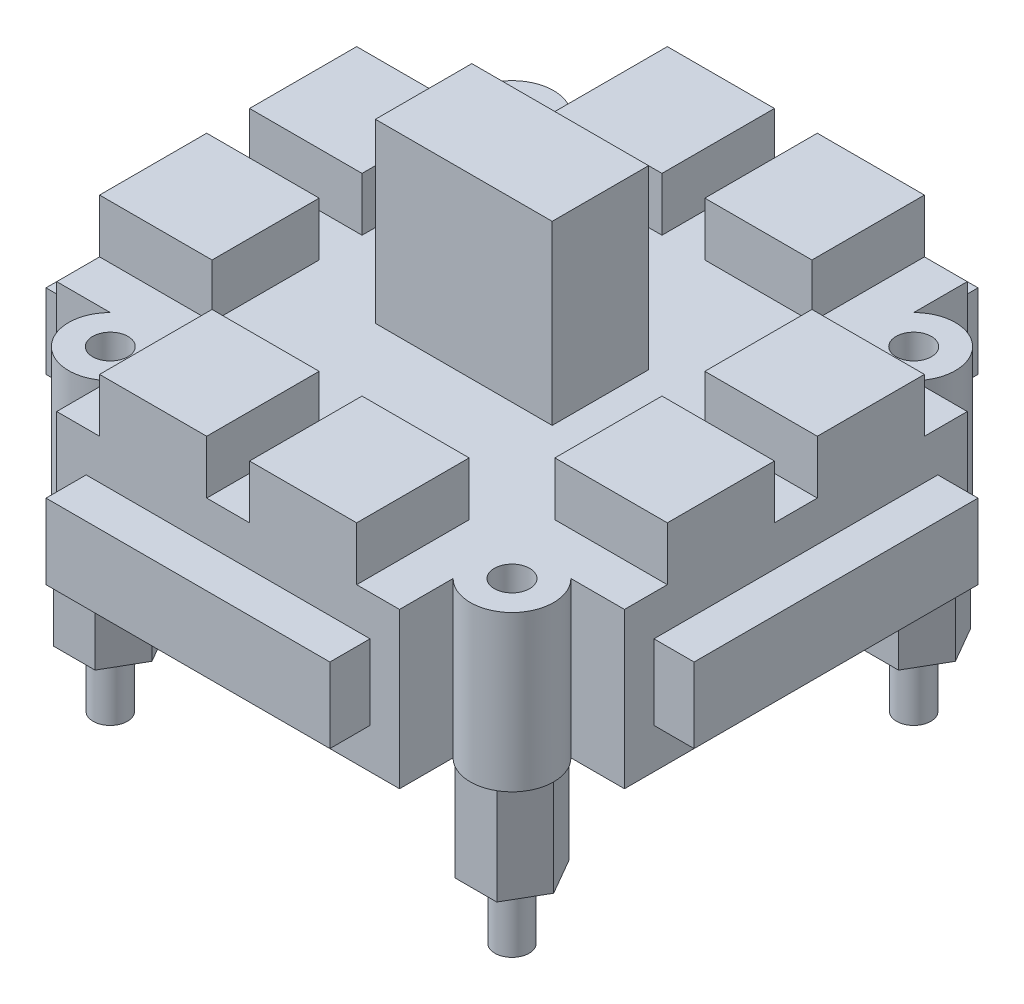
SolidWorks part; units mm, degrees
ref_plane "前视基准面" through (0, 0, 0) normal (0, 0, 1) x (1, 0, 0)
ref_plane "上视基准面" through (0, 0, 0) normal (0, 1, 0) x (1, 0, 0)
ref_plane "右视基准面" through (0, 0, 0) normal (1, 0, 0) x (0, 0, -1)
other "Configuration Table"
sketch "草图1" plane through (0, 0, 0) normal (0, 1, 0) x (1, 0, 0)
  line L1 (-18.75, -18.75) -> (18.75, -18.75) construction
  line L2 (-18.75, -18.75) -> (-18.75, 18.75) construction
  line L3 (-18.75, 18.75) -> (18.75, 18.75) construction
  line L4 (18.75, -18.75) -> (18.75, 18.75) construction
  line L5 (-18.75, -18.75) -> (18.75, 18.75) construction
  line L6 (-18.75, 18.75) -> (18.75, -18.75) construction
  line L7 (-16, -26.5) -> (16, -26.5) construction
  line L8 (-16, -26.5) -> (-16, 26.5) construction
  line L9 (-16, 26.5) -> (16, 26.5) construction
  line L10 (16, -26.5) -> (16, 26.5) construction
  line L11 (-16, -26.5) -> (16, 26.5) construction
  line L12 (-16, 26.5) -> (16, -26.5) construction
  line L13 (-26.5, -16) -> (26.5, -16) construction
  line L14 (-26.5, -16) -> (-26.5, 16) construction
  line L15 (-26.5, 16) -> (26.5, 16) construction
  line L16 (26.5, -16) -> (26.5, 16) construction
  line L17 (-26.5, -16) -> (26.5, 16) construction
  line L18 (-26.5, 16) -> (26.5, -16) construction
  circle A0 centre (-18.75, 18.75) radius 1.65
  circle A1 centre (18.75, 18.75) radius 1.65
  circle A2 centre (18.75, -18.75) radius 1.65
  circle A3 centre (-18.75, -18.75) radius 1.65
  circle A4 centre (-18.75, 18.75) radius 3.8891
  circle A5 centre (18.75, 18.75) radius 3.8891
  circle A6 centre (18.75, -18.75) radius 3.8891
  circle A7 centre (-18.75, -18.75) radius 3.8891
  point P0 (0, 0)
  point P10 (0, 0)
  point P15 (0, 0)
  point P24 (-16, 16)
  dimension "D3" = 3.3
  dimension "D1" = 37.5
  dimension "D2" = 37.5
  dimension "D4" = 32
  dimension "D5" = 53
  dimension "D6" = 32
  dimension "D7" = 53
extrude "凸台-拉伸2" add sketch "草图1" along normal mid plane 14.5
sketch "草图2" plane through (0, 0, 0) normal (0, 1, 0) x (1, 0, 0)
  line L1 (-16, -26.5) -> (16, -26.5)
  line L2 (-16, -26.5) -> (-16, 26.5)
  line L3 (-16, 26.5) -> (16, 26.5)
  line L4 (16, -26.5) -> (16, 26.5)
  line L5 (-16, -26.5) -> (16, 26.5) construction
  line L6 (-16, 26.5) -> (16, -26.5) construction
  line L7 (-26.5, -16) -> (26.5, -16)
  line L8 (-26.5, -16) -> (-26.5, 16)
  line L9 (-26.5, 16) -> (26.5, 16)
  line L10 (26.5, -16) -> (26.5, 16)
  line L11 (-26.5, -16) -> (26.5, 16) construction
  line L12 (-26.5, 16) -> (26.5, -16) construction
  circle A1 centre (-18.75, -18.75) radius 1.65
  circle A2 centre (-18.75, -18.75) radius 1.65 construction
  circle A3 centre (18.75, -18.75) radius 1.65
  circle A4 centre (18.75, -18.75) radius 1.65 construction
  circle A5 centre (18.75, 18.75) radius 1.65
  circle A6 centre (18.75, 18.75) radius 1.65 construction
  circle A7 centre (-18.75, 18.75) radius 1.65
  circle A8 centre (-18.75, 18.75) radius 1.65 construction
  circle A9 centre (-18.75, -18.75) radius 3.8891
  circle A10 centre (-18.75, -18.75) radius 3.8891 construction
  circle A11 centre (18.75, -18.75) radius 3.8891
  circle A12 centre (18.75, -18.75) radius 3.8891 construction
  circle A13 centre (18.75, 18.75) radius 3.8891
  circle A14 centre (18.75, 18.75) radius 3.8891 construction
  circle A15 centre (-18.75, 18.75) radius 3.8891
  circle A16 centre (-18.75, 18.75) radius 3.8891 construction
  point P0 (0, 0)
  point P6 (0, 0)
  dimension "D9" = 32
  dimension "D10" = 53
  dimension "D11" = 32
  dimension "D12" = 53
  dimension "D1" = 0
  dimension "D2" = 0
  dimension "D3" = 0
  dimension "D4" = 0
  dimension "D5" = 0
  dimension "D6" = 0
  dimension "D7" = 0
  dimension "D8" = 0
extrude "凸台-拉伸3" add sketch "草图2" along normal mid plane 14.5 contours L9 L8 L7 L2 | L9 L2 L7 L4 | L2 L9 L4 L3 | L7 L10 L9 L4 | L7 L2 L1 L4
sketch "草图3" plane through (0, 0, 0) normal (0, 1, 0) x (1, 0, 0)
  line L1 (-13.25, -30.25) -> (13.25, -30.25)
  line L2 (-13.25, -30.25) -> (-13.25, 30.25)
  line L3 (-13.25, 30.25) -> (13.25, 30.25)
  line L4 (13.25, -30.25) -> (13.25, 30.25)
  line L5 (-13.25, -30.25) -> (13.25, 30.25) construction
  line L6 (-13.25, 30.25) -> (13.25, -30.25) construction
  line L7 (-30.25, -13.25) -> (30.25, -13.25)
  line L8 (-30.25, -13.25) -> (-30.25, 13.25)
  line L9 (-30.25, 13.25) -> (30.25, 13.25)
  line L10 (30.25, -13.25) -> (30.25, 13.25)
  line L11 (-30.25, -13.25) -> (30.25, 13.25) construction
  line L12 (-30.25, 13.25) -> (30.25, -13.25) construction
  point P0 (0, 0)
  point P6 (0, 0)
  dimension "D1" = 26.5
  dimension "D2" = 60.5
  dimension "D3" = 26.5
  dimension "D4" = 60.5
extrude "凸台-拉伸4" add sketch "草图3" along normal mid plane 7 contours L7 L2 L1 L4 | L9 L8 L7 L2 | L2 L9 L4 L3
sketch "草图4" plane through (0, 7.25, 0) normal (0, 1, 0) x (1, 0, 0)
  line L1 (-8.25, -4.5) -> (8.25, -4.5)
  line L2 (-8.25, -4.5) -> (-8.25, 4.5)
  line L3 (-8.25, 4.5) -> (8.25, 4.5)
  line L4 (8.25, -4.5) -> (8.25, 4.5)
  line L5 (-8.25, -4.5) -> (8.25, 4.5) construction
  line L6 (-8.25, 4.5) -> (8.25, -4.5) construction
  point P0 (0, 0)
  dimension "D1" = 16.5
  dimension "D2" = 9
extrude "凸台-拉伸5" add sketch "草图4" along normal blind 16.5
sketch "草图5" plane through (0, 7.25, 0) normal (0, 1, 0) x (1, 0, 0)
  line L0 (-8.25, 0) -> (-26.5, 0) construction
  line L1 (-8.25, 4.5) -> (-8.25, -4.5) construction
  line L2 (-26.5, -16) -> (-26.5, 16) construction
  line L3 (-26.5, -13.25) -> (-26.5, 13.25) construction
  line L4 (-26.5, 2) -> (-16, 2)
  line L5 (-26.5, 2) -> (-26.5, 12)
  line L6 (-26.5, 12) -> (-16, 12)
  line L7 (-16, 2) -> (-16, 12)
  line L8 (-26.5, -12) -> (-16, -12)
  line L9 (-16, -2) -> (-16, -12)
  line L10 (-26.5, -2) -> (-16, -2)
  line L11 (-26.5, -2) -> (-26.5, -12)
  line L12 (2, 26.5) -> (12, 26.5)
  line L13 (2, 26.5) -> (2, 16)
  line L14 (2, 16) -> (12, 16)
  line L15 (12, 26.5) -> (12, 16)
  line L16 (-12, 26.5) -> (-12, 16)
  line L17 (-2, 16) -> (-12, 16)
  line L18 (-2, 26.5) -> (-2, 16)
  line L19 (-2, 26.5) -> (-12, 26.5)
  line L20 (26.5, -2) -> (26.5, -12)
  line L21 (26.5, -2) -> (16, -2)
  line L22 (16, -2) -> (16, -12)
  line L23 (26.5, -12) -> (16, -12)
  line L24 (26.5, 12) -> (16, 12)
  line L25 (16, 2) -> (16, 12)
  line L26 (26.5, 2) -> (16, 2)
  line L27 (26.5, 2) -> (26.5, 12)
  line L28 (-2, -26.5) -> (-12, -26.5)
  line L29 (-2, -26.5) -> (-2, -16)
  line L30 (-2, -16) -> (-12, -16)
  line L31 (-12, -26.5) -> (-12, -16)
  line L32 (12, -26.5) -> (12, -16)
  line L33 (2, -16) -> (12, -16)
  line L34 (2, -26.5) -> (2, -16)
  line L35 (2, -26.5) -> (12, -26.5)
  line L36 (-8.25, 0) -> (-16, 2) construction
  line L37 (-8.25, 0) -> (2, 16) construction
  dimension "D1" = 10
  dimension "D2" = 10.5
  dimension "D3" = 4
  dimension "D5" = 108.174
  dimension "D6" = 16.1245
  dimension "D4" = 4
extrude "凸台-拉伸6" add sketch "草图5" along normal blind 5
sketch "草图6" plane through (0, -7.25, 0) normal (0, -1, 0) x (1, 0, 0)
  line L0 (-18.75, 18.75) -> (-14.8609, 18.75) construction
  line L1 (-14.8609, 18.75) -> (-16.8055, 22.118)
  line L2 (-16.8055, 22.118) -> (-20.6945, 22.118)
  line L3 (-20.6945, 22.118) -> (-22.6391, 18.75)
  line L4 (-22.6391, 18.75) -> (-20.6945, 15.382)
  line L5 (-20.6945, 15.382) -> (-16.8055, 15.382)
  line L6 (-16.8055, 15.382) -> (-14.8609, 18.75)
  line L7 (22.6391, 18.75) -> (20.6945, 22.118)
  line L8 (20.6945, 22.118) -> (16.8055, 22.118)
  line L9 (16.8055, 22.118) -> (14.8609, 18.75)
  line L10 (14.8609, 18.75) -> (16.8055, 15.382)
  line L11 (16.8055, 15.382) -> (20.6945, 15.382)
  line L12 (20.6945, 15.382) -> (22.6391, 18.75)
  line L13 (18.75, 18.75) -> (22.6391, 18.75) construction
  line L14 (22.6391, -18.75) -> (20.6945, -15.382)
  line L15 (20.6945, -15.382) -> (16.8055, -15.382)
  line L16 (16.8055, -15.382) -> (14.8609, -18.75)
  line L17 (14.8609, -18.75) -> (16.8055, -22.118)
  line L18 (16.8055, -22.118) -> (20.6945, -22.118)
  line L19 (20.6945, -22.118) -> (22.6391, -18.75)
  line L20 (18.75, -18.75) -> (22.6391, -18.75) construction
  line L21 (-14.8609, -18.75) -> (-16.8055, -15.382)
  line L22 (-16.8055, -15.382) -> (-20.6945, -15.382)
  line L23 (-20.6945, -15.382) -> (-22.6391, -18.75)
  line L24 (-22.6391, -18.75) -> (-20.6945, -22.118)
  line L25 (-20.6945, -22.118) -> (-16.8055, -22.118)
  line L26 (-16.8055, -22.118) -> (-14.8609, -18.75)
  line L27 (-18.75, -18.75) -> (-14.8609, -18.75) construction
  circle A1 centre (-18.75, 18.75) radius 3.368 construction
  arc A2 (-16, 21.5) -> (-21.5, 16) centre (-18.75, 18.75) ccw construction
  circle A3 centre (18.75, 18.75) radius 3.368 construction
  circle A4 centre (18.75, -18.75) radius 3.368 construction
  circle A5 centre (-18.75, -18.75) radius 3.368 construction
  dimension "D1" = 2
  dimension "D2" = 2
extrude "凸台-拉伸7" add sketch "草图6" along normal blind 9
sketch "草图7" plane through (0, -16.25, 0) normal (0, -1, 0) x (1, 0, 0)
  circle A0 centre (-18.75, 18.75) radius 1.6
  circle A1 centre (18.75, 18.75) radius 1.6
  circle A2 centre (18.75, -18.75) radius 1.6
  circle A3 centre (-18.75, -18.75) radius 1.6
  dimension "D1" = 3.2
extrude "凸台-拉伸8" add sketch "草图7" along normal blind 6
cosmetic thread "装饰螺纹线1" parameters "D2"=2.2
cosmetic thread "装饰螺纹线2" parameters "D2"=2.2
cosmetic thread "装饰螺纹线3" parameters "D2"=2.2
cosmetic thread "装饰螺纹线4" parameters "D2"=2.2
